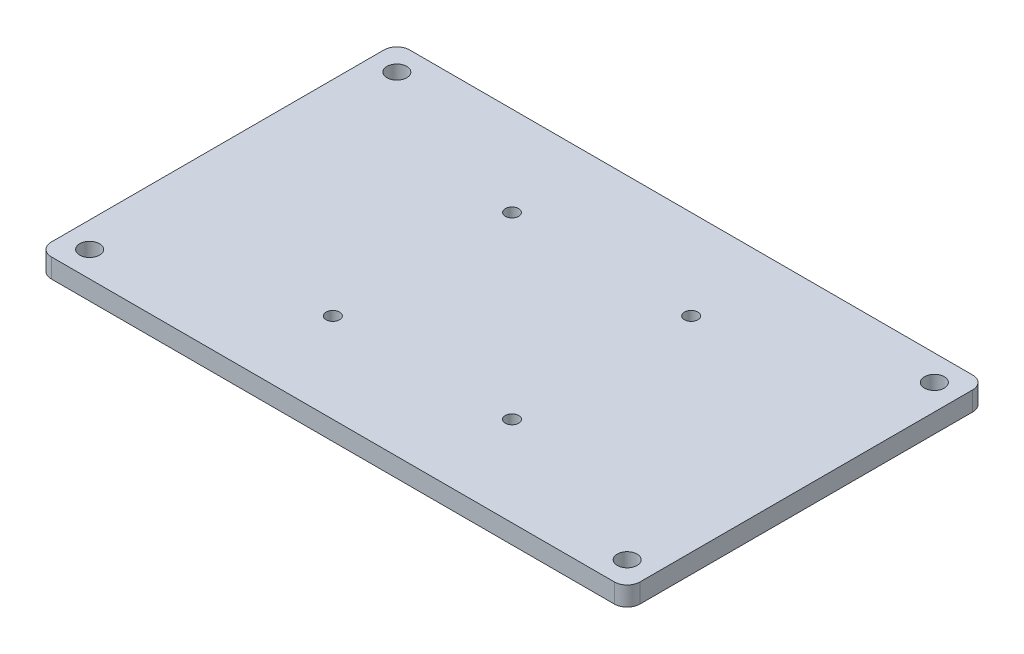
SolidWorks part; units mm, degrees
ref_plane "Front Plane" through (0, 0, 0) normal (0, 0, 1) x (1, 0, 0)
ref_plane "Top Plane" through (0, 0, 0) normal (0, 1, 0) x (1, 0, 0)
ref_plane "Right Plane" through (0, 0, 0) normal (1, 0, 0) x (0, 0, -1)
sketch "Sketch1" plane through (0, 0, 0) normal (0, 1, 0) x (1, 0, 0)
  line L0 (-28.6497, 0) -> (12.4645, 0) construction
  line L1 (-44, 28) -> (44, 28)
  line L2 (-46, 26) -> (-46, -26)
  line L3 (-44, -28) -> (44, -28)
  line L4 (46, 26) -> (46, -26)
  line L5 (-46, 28) -> (46, -28) construction
  line L6 (-46, -28) -> (46, 28) construction
  line L7 (0, -8.2787) -> (0, 17.2084) construction
  circle A0 centre (42, 24) radius 1.55
  arc A1 (44, -28) -> (46, -26) centre (44, -26) ccw
  arc A2 (-46, -26) -> (-44, -28) centre (-44, -26) ccw
  arc A3 (-44, 28) -> (-46, 26) centre (-44, 26) ccw
  arc A4 (44, 28) -> (46, 26) centre (44, 26) cw
  circle A5 centre (-42, 24) radius 1.55
  circle A6 centre (42, -24) radius 1.55
  circle A7 centre (-42, -24) radius 1.55
  circle A8 centre (14, 14) radius 1.05
  circle A9 centre (14, -14) radius 1.05
  circle A10 centre (-14, 14) radius 1.05
  circle A11 centre (-14, -14) radius 1.05
  point P0 (0, 0)
  dimension "D3" = 24
  dimension "D4" = 42
  dimension "D5" = 3.1
  dimension "D6" = 2
  dimension "D7" = 14
  dimension "D8" = 14
  dimension "D9" = 2.1
  dimension "D1" = 56
  dimension "D2" = 92
extrude "Boss-Extrude1" add sketch "Sketch1" along normal blind 3
